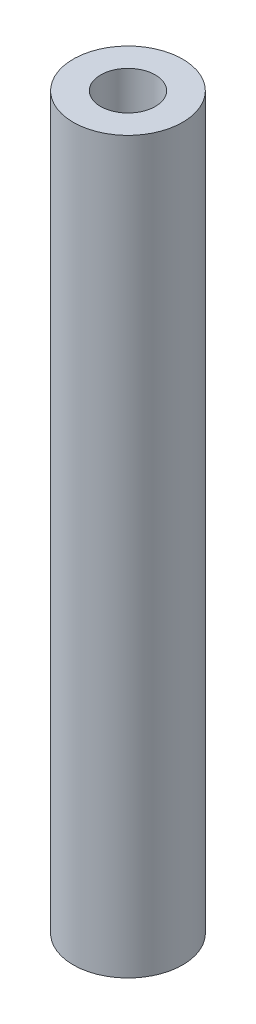
SolidWorks part; units mm, degrees
ref_plane "前视基准面" through (0, 0, 0) normal (0, 0, 1) x (1, 0, 0)
ref_plane "上视基准面" through (0, 0, 0) normal (0, 1, 0) x (1, 0, 0)
ref_plane "右视基准面" through (0, 0, 0) normal (1, 0, 0) x (0, 0, -1)
sketch "Sketch1" plane through (0, 0, 0) normal (0, 1, 0) x (1, 0, 0)
  circle A0 centre (0, 0) radius 1.5
  circle A1 centre (0, 0) radius 3
  dimension "D1" = 3
  dimension "D2" = 6
extrude "Boss-Extrude1" add sketch "Sketch1" along normal blind 40
